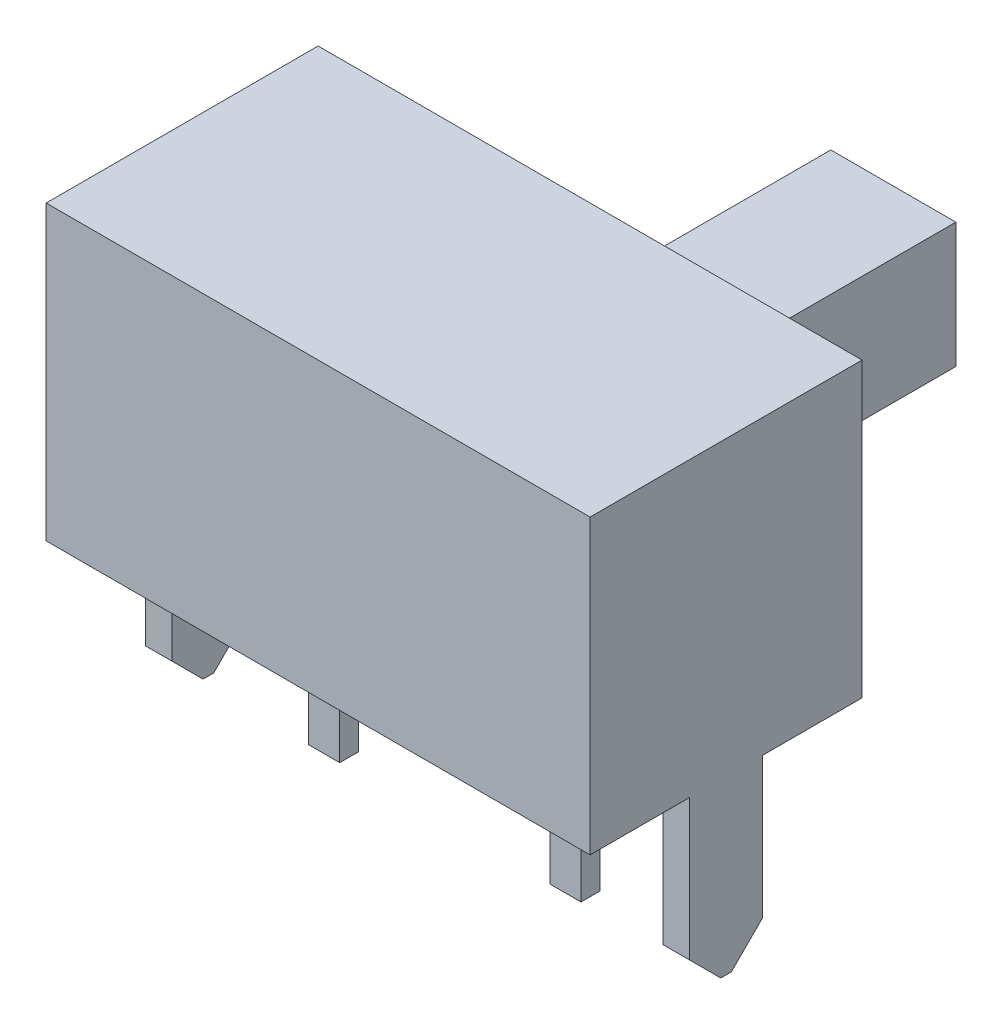
SolidWorks part; units mm, degrees
ref_plane "Front Plane" through (0, 0, 0) normal (0, 0, 1) x (1, 0, 0)
ref_plane "Top Plane" through (0, 0, 0) normal (0, 1, 0) x (1, 0, 0)
ref_plane "Right Plane" through (0, 0, 0) normal (1, 0, 0) x (0, 0, -1)
sketch "Sketch1" plane through (0, 0, 0) normal (0, 1, 0) x (1, 0, 0)
  line L1 (-4.35, -2.175) -> (4.35, -2.175)
  line L2 (-4.35, -2.175) -> (-4.35, 2.175)
  line L3 (-4.35, 2.175) -> (4.35, 2.175)
  line L4 (4.35, -2.175) -> (4.35, 2.175)
  line L5 (-4.35, -2.175) -> (4.35, 2.175) construction
  line L6 (-4.35, 2.175) -> (4.35, -2.175) construction
  point P0 (0, 0)
  dimension "D1" = 8.7
  dimension "D2" = 4.35
extrude "Boss-Extrude1" add sketch "Sketch1" along normal blind 4.68
sketch "Sketch3" plane through (0, 0, -2.175) normal (0, 0, -1) x (-1, 0, 0)
  line L0 (-4.35, 2.34) -> (4.35, 2.34) construction
  line L1 (-4.35, 4.68) -> (-4.35, 0) construction
  line L2 (4.35, 4.68) -> (4.35, 0) construction
  line L4 (-1.85, 1.34) -> (0.15, 1.34)
  line L5 (-1.85, 1.34) -> (-1.85, 3.34)
  line L6 (-1.85, 3.34) -> (0.15, 3.34)
  line L7 (0.15, 1.34) -> (0.15, 3.34)
  line L8 (-1.85, 1.34) -> (0.15, 3.34) construction
  line L9 (-1.85, 3.34) -> (0.15, 1.34) construction
  point P6 (-0.85, 2.34)
  dimension "D1" = 2
  dimension "D2" = 2.5
extrude "Boss-Extrude3" add sketch "Sketch3" along normal blind 4
sketch "Sketch4" plane through (0, 0, 0) normal (0, -1, 0) x (1, 0, 0)
  line L0 (-4.35, 0) -> (4.35, 0) construction
  line L1 (-4.35, -2.175) -> (-4.35, 2.175) construction
  line L2 (4.35, 2.175) -> (4.35, -2.175) construction
  line L3 (0, 0) -> (0, 2.175) construction
  line L4 (-4.35, 2.175) -> (4.35, 2.175) construction
  line L6 (3.93, -0.585) -> (4.35, -0.585)
  line L7 (3.93, -0.585) -> (3.93, 0.585)
  line L8 (3.93, 0.585) -> (4.35, 0.585)
  line L9 (4.35, -0.585) -> (4.35, 0.585)
  line L10 (3.93, -0.585) -> (4.35, 0.585) construction
  line L11 (3.93, 0.585) -> (4.35, -0.585) construction
  line L12 (2.18, 0.15) -> (1.68, 0.15)
  line L13 (2.18, 0.15) -> (2.18, -0.15)
  line L14 (2.18, -0.15) -> (1.68, -0.15)
  line L15 (1.68, 0.15) -> (1.68, -0.15)
  line L16 (2.18, 0.15) -> (1.68, -0.15) construction
  line L17 (2.18, -0.15) -> (1.68, 0.15) construction
  point P11 (4.14, 0)
  point P16 (1.93, 0)
  dimension "D1" = 0.42
  dimension "D2" = 1.17
  dimension "D3" = 0.5
  dimension "D4" = 0.3
  dimension "D5" = 1.75
extrude "Boss-Extrude4" add sketch "Sketch4" along normal blind 2.75
chamfer "Chamfer1" distance 0.5 angle 45 2 edges at (4.14, -2.75, 0.585) (4.14, -2.75, -0.585)
ref_plane "Plane1" through (0, 0, 0) normal (1, 0, 0) x (0, 0, -1)
mirror "Mirror1" about plane through (0, 0, 0) normal (1, 0, 0) of "Chamfer1", "Boss-Extrude4"
